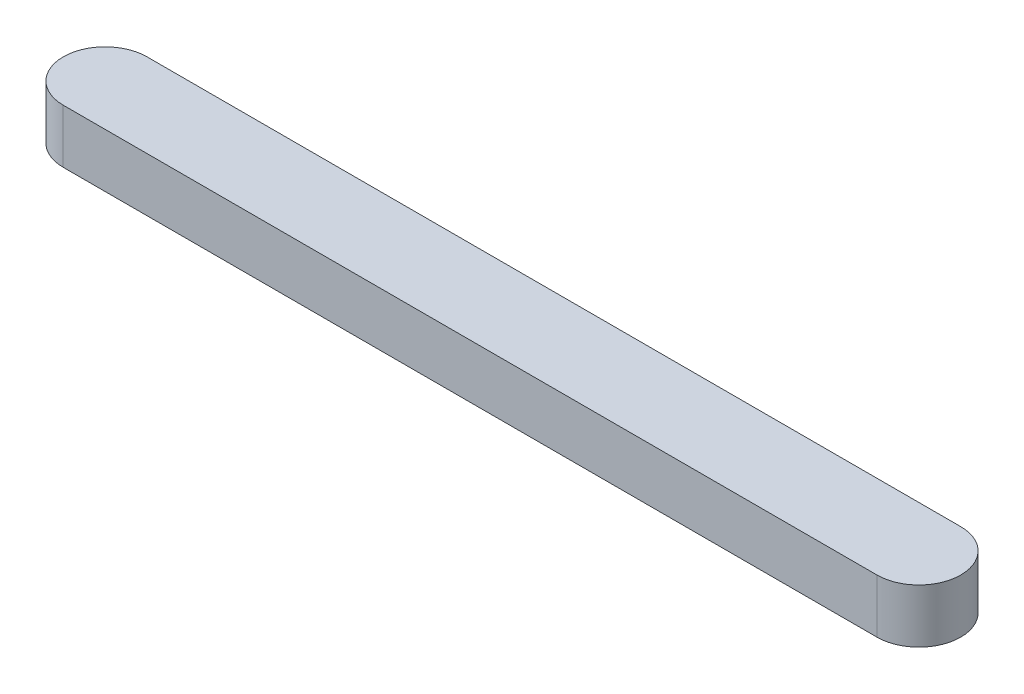
SolidWorks part; units mm, degrees
ref_plane "Спереди" through (0, 0, 0) normal (0, 0, 1) x (1, 0, 0)
ref_plane "Сверху" through (0, 0, 0) normal (0, 1, 0) x (1, 0, 0)
ref_plane "Справа" through (0, 0, 0) normal (1, 0, 0) x (0, 0, -1)
other "Configuration Table"
sketch "Эскиз1" plane through (0, 0, 0) normal (0, 1, 0) x (1, 0, 0)
  line L0 (-68, 0) -> (68, 0) construction
  line L1 (-68, 7) -> (68, 7)
  line L2 (-68, -7) -> (68, -7)
  arc A0 (-68, 7) -> (-68, -7) centre (-68, 0) ccw
  arc A1 (68, -7) -> (68, 7) centre (68, 0) ccw
  point P2 (0, 0)
  dimension "D1" = 150
  dimension "D2" = 7
  dimension "D3" = 14
extrude "Бобышка-Вытянуть1" add sketch "Эскиз1" along normal blind 9
